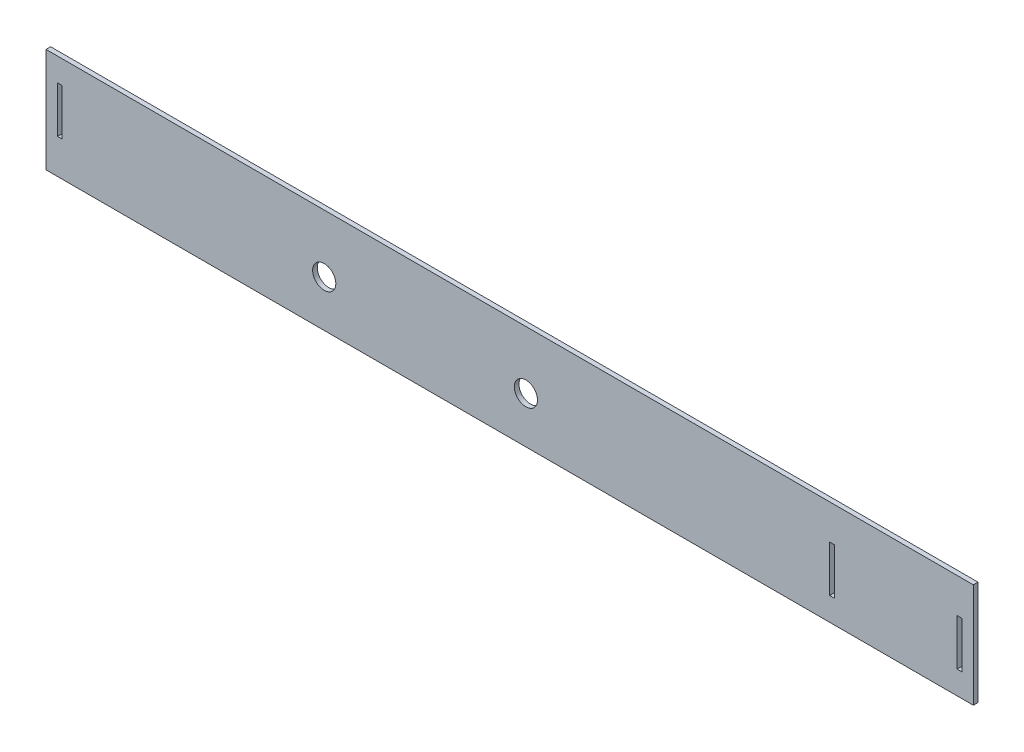
SolidWorks part; units mm, degrees
ref_plane "Спереди" through (0, 0, 0) normal (0, 0, 1) x (1, 0, 0)
ref_plane "Сверху" through (0, 0, 0) normal (0, 1, 0) x (1, 0, 0)
ref_plane "Справа" through (0, 0, 0) normal (1, 0, 0) x (0, 0, -1)
sketch "Эскиз1" plane through (0, 0, 0) normal (0, 0, 1) x (1, 0, 0)
  line L1 (0, 0) -> (400, 0)
  line L2 (0, 0) -> (0, 45)
  line L3 (0, 45) -> (400, 45)
  line L4 (400, 0) -> (400, 45)
  line L5 (338, 30) -> (340, 30)
  line L6 (338, 30) -> (338, 10)
  line L7 (338, 10) -> (340, 10)
  line L8 (340, 30) -> (340, 10)
  line L13 (5, 35) -> (7, 35)
  line L14 (5, 35) -> (5, 15)
  line L15 (5, 15) -> (7, 15)
  line L16 (7, 35) -> (7, 15)
  line L17 (393, 30) -> (395, 30)
  line L18 (393, 30) -> (393, 10)
  line L19 (393, 10) -> (395, 10)
  line L20 (395, 30) -> (395, 10)
  circle A0 centre (120, 20) radius 5
  circle A1 centre (207, 20) radius 5
  dimension "D5" = 10
  dimension "D6" = 10
  dimension "D1" = 400
  dimension "D2" = 45
  dimension "D3" = 120
  dimension "D4" = 207
  dimension "D7" = 2
  dimension "D8" = 2
  dimension "D9" = 20
  dimension "D10" = 5
  dimension "D11" = 60
  dimension "D12" = 20
  dimension "D13" = 10
  dimension "D14" = 25
  dimension "D15" = 25
  dimension "D16" = 2
  dimension "D17" = 20
  dimension "D18" = 10
  dimension "D19" = 5
  dimension "D20" = 10
extrude "Бобышка-Вытянуть1" add sketch "Эскиз1" along normal blind 2
